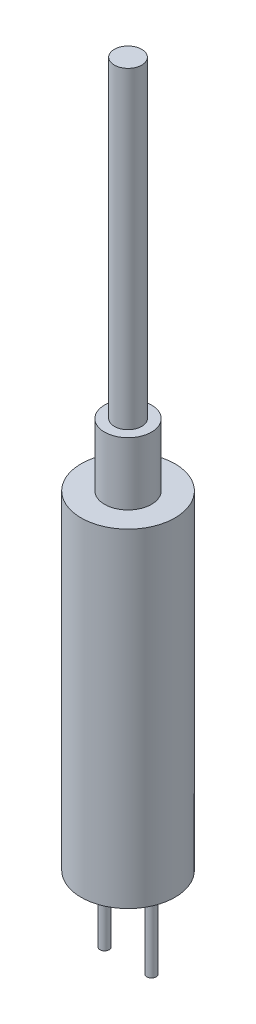
SolidWorks part; units mm, degrees
ref_plane "Front Plane" through (0, 0, 0) normal (0, 0, 1) x (1, 0, 0)
ref_plane "Top Plane" through (0, 0, 0) normal (0, 1, 0) x (1, 0, 0)
ref_plane "Right Plane" through (0, 0, 0) normal (1, 0, 0) x (0, 0, -1)
sketch "SK Electrode pins" plane through (0, 0, 0) normal (0, 1, 0) x (1, 0, 0)
  circle A0 centre (-3, 0) radius 0.6
  circle A1 centre (3, 0) radius 0.6
extrude "Electrode pins" add sketch "SK Electrode pins" along normal blind 10 separate body
sketch "SK Probe body" plane through (0, 0, 0) normal (0, 1, 0) x (1, 0, 0)
  circle A0 centre (0, 0) radius 6
extrude "Probe body" add sketch "SK Probe body" along normal blind 42 from offset 10 separate body
sketch "SK Strain relief" plane through (0, 0, 0) normal (0, 1, 0) x (1, 0, 0)
  circle A0 centre (0, 0) radius 3
extrude "Strain relief" add sketch "SK Strain relief" along normal blind 8 from offset 52 separate body
sketch "SK Cable" plane through (0, 0, 0) normal (0, 1, 0) x (1, 0, 0)
  circle A0 centre (0, 0) radius 1.75
extrude "Cable" add sketch "SK Cable" along normal blind 40 from offset 60 separate body
